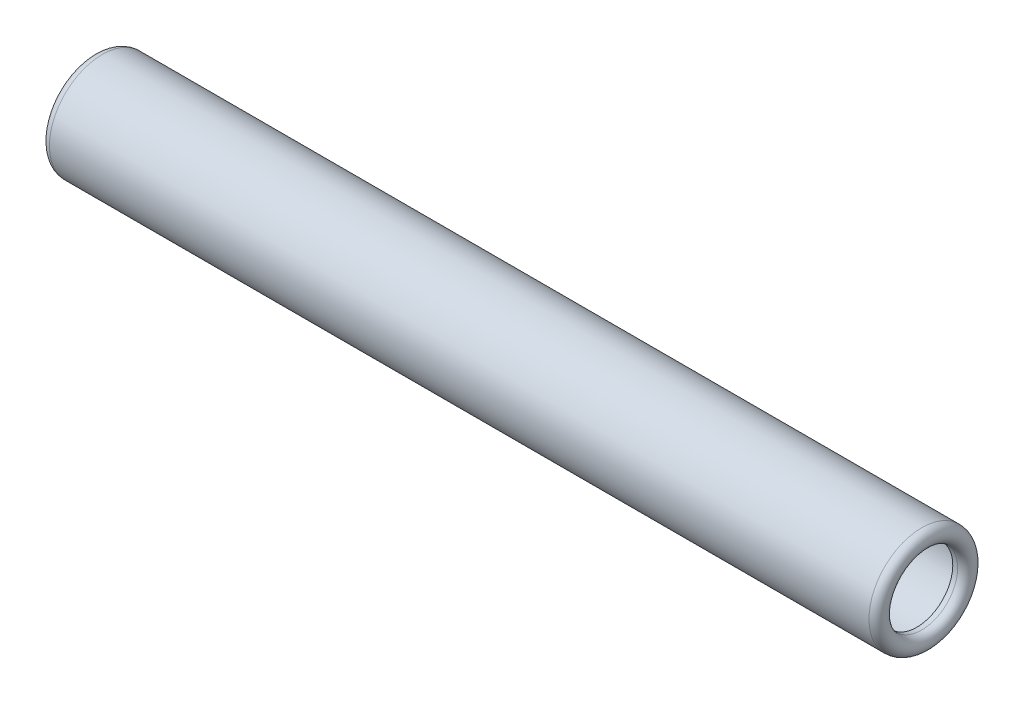
SolidWorks part; units mm, degrees
ref_plane "Front Plane" through (0, 0, 0) normal (0, 0, 1) x (1, 0, 0)
ref_plane "Top Plane" through (0, 0, 0) normal (0, 1, 0) x (1, 0, 0)
ref_plane "Right Plane" through (0, 0, 0) normal (1, 0, 0) x (0, 0, -1)
sketch "Sketch1" plane through (0, 0, 0) normal (0, 0, 1) x (1, 0, 0)
  line L0 (4.8, 12.95) -> (4.8, 14.15)
  line L1 (-5.5, 0) -> (-5.5, 19.05) construction
  line L2 (298.95, 12.95) -> (297.2, 12.95)
  line L3 (298.95, 14.15) -> (297.2, 14.15)
  line L5 (298.95, 19.05) -> (3.05, 19.05)
  line L6 (297.2, 12.95) -> (297.2, 14.15)
  line L7 (307.5, 0) -> (307.5, 19.05) construction
  line L8 (307.5, 0) -> (-5.5, 0) construction
  line L9 (298.95, 17.85) -> (3.05, 17.85)
  line L10 (298.95, 19.05) -> (195.8641, 19.05) construction
  line L11 (303.0342, 13.8) -> (298.4927, 17.85) construction
  line L12 (197.0641, 17.85) -> (197.0641, 13.8) construction
  line L14 (190.8641, 12.6) -> (303.8641, 12.6) construction
  line L15 (195.8641, 14.08) -> (190.8641, 14.08) construction
  line L17 (303.0342, 13.8) -> (303.0342, 13.8) construction
  line L18 (303.0342, 13.8) -> (303.0342, 13.8) construction
  line L19 (197.0641, 13.8) -> (197.0641, 13.8) construction
  line L20 (197.0641, 13.8) -> (197.0641, 13.8) construction
  line L21 (197.0641, 13.8) -> (303.0342, 13.8) construction
  line L22 (3.05, 14.15) -> (4.8, 14.15)
  line L24 (3.05, 12.95) -> (4.8, 12.95)
  line L25 (195.8641, 19.05) -> (195.8641, 14.08) construction
  line L26 (298.4927, 17.85) -> (197.0641, 17.85) construction
  line L31 (190.8641, 14.08) -> (190.8641, 12.6) construction
  line L32 (304.3528, 13.8957) -> (304.7298, 13.8957) construction
  line L33 (303.8641, 12.6) -> (304.3528, 13.8957) construction
  line L34 (304.7298, 13.8957) -> (298.95, 19.05) construction
  arc A0 (3.05, 17.85) -> (3.05, 14.15) centre (3.05, 16) ccw
  arc A1 (3.05, 19.05) -> (3.05, 12.95) centre (3.05, 16) ccw
  arc A2 (298.95, 19.05) -> (298.95, 12.95) centre (298.95, 16) cw
  arc A3 (298.95, 17.85) -> (298.95, 14.15) centre (298.95, 16) cw
  point P8 (0, 16)
  point P35 (302, 16)
  dimension "MSM_3" = 3.7
  dimension "L" = 313
  dimension "D" = 38.1
  dimension "MSM_1" = 4.8
  dimension "MSM_2" = 4.8
  dimension "T_s" = 1.2
revolve "Revolve1" add sketch "Sketch1" angle 360 about L8
